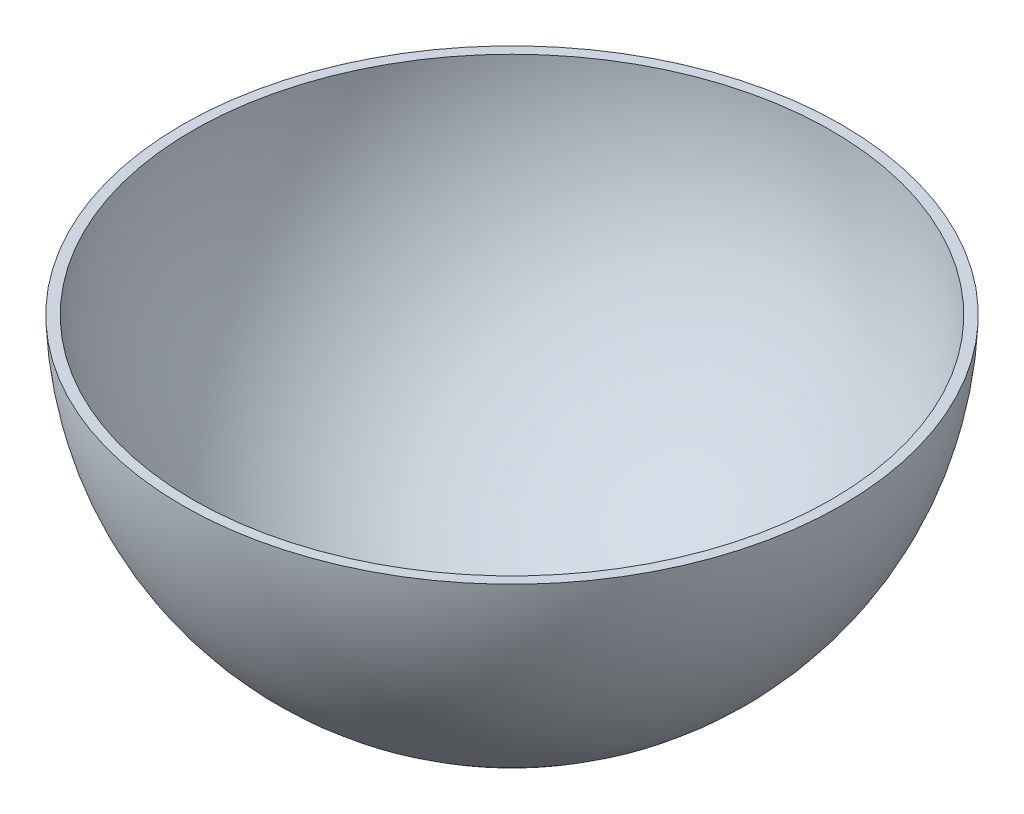
SolidWorks part; units mm, degrees
ref_plane "Front Plane" through (0, 0, 0) normal (0, 0, 1) x (1, 0, 0)
ref_plane "Top Plane" through (0, 0, 0) normal (0, 1, 0) x (1, 0, 0)
ref_plane "Right Plane" through (0, 0, 0) normal (1, 0, 0) x (0, 0, -1)
sketch "Sketch1" plane through (0, 0, 0) normal (0, 0, 1) x (1, 0, 0)
  line L0 (0, 0) -> (258, 0)
  line L1 (0, -248.9997) -> (0, 0)
  arc A0 (258, 0) -> (0, -248.9997) centre (0, 9.163) cw
revolve "BowlRevolve" add sketch "Sketch1" angle 360 about L1
shell "Shell1" thickness 8
